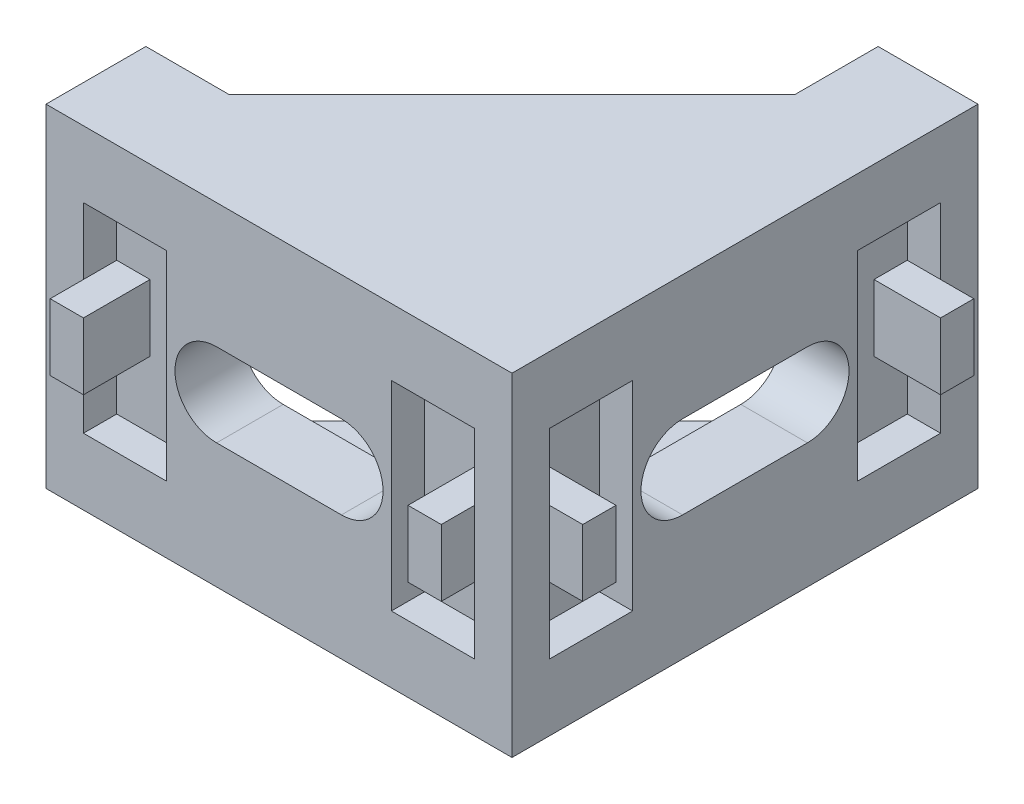
SolidWorks part; units mm, degrees
ref_plane "Front Plane" through (0, 0, 0) normal (0, 0, 1) x (1, 0, 0)
ref_plane "Top Plane" through (0, 0, 0) normal (0, 1, 0) x (1, 0, 0)
ref_plane "Right Plane" through (0, 0, 0) normal (1, 0, 0) x (0, 0, -1)
sketch "Sketch1" plane through (0, 0, 0) normal (0, 1, 0) x (1, 0, 0)
  line L0 (-28, 0) -> (0, 0)
  line L1 (0, 0) -> (0, 28)
  line L2 (0, 28) -> (-6, 28)
  line L3 (-6, 28) -> (-6, 23)
  line L4 (-6, 23) -> (-23, 6)
  line L5 (-23, 6) -> (-28, 6)
  line L6 (-28, 6) -> (-28, 0)
  dimension "D1" = 28
  dimension "D2" = 28
  dimension "D3" = 6
  dimension "D4" = 6
  dimension "D5" = 5
  dimension "D6" = 5
extrude "Boss-Extrude1" add sketch "Sketch1" along normal blind 20
sketch "Sketch2" plane through (0, 0, -28) normal (0, 0, -1) x (-1, 0, 0)
  line L0 (0, 0) -> (6, 0) construction
  line L1 (4, 17) -> (28, 17)
  line L2 (4, 17) -> (4, 3)
  line L3 (4, 3) -> (28, 3)
  line L4 (28, 17) -> (28, 3)
  line L5 (6, 20) -> (23, 20) construction
  line L6 (6, 20) -> (6, 0) construction
  line L7 (23, 20) -> (23, 0) construction
  dimension "D1" = 3
  dimension "D2" = 3
  dimension "D3" = 2
  dimension "D4" = 5
extrude "Cut-Extrude1" cut sketch "Sketch2" against normal blind 24
sketch "Sketch3" plane through (0, 0, 0) normal (0, 0, 1) x (1, 0, 0)
  line L0 (-28, 20) -> (-28, 0) construction
  line L1 (-25.75, 4) -> (-20.75, 4)
  line L2 (-25.75, 4) -> (-25.75, 16)
  line L3 (-25.75, 16) -> (-20.75, 16)
  line L4 (-20.75, 4) -> (-20.75, 16)
  line L5 (-28, 20) -> (0, 20) construction
  line L6 (-28, 0) -> (0, 0) construction
  line L7 (-14, 20) -> (-14, 0) construction
  line L8 (-7.25, 4) -> (-7.25, 16)
  line L9 (-2.25, 16) -> (-7.25, 16)
  line L10 (-2.25, 4) -> (-2.25, 16)
  line L11 (-2.25, 4) -> (-7.25, 4)
  dimension "D1" = 2.25
  dimension "D2" = 4
  dimension "D3" = 4
  dimension "D4" = 5
extrude "Cut-Extrude2" cut sketch "Sketch3" against normal blind 2
sketch "Sketch4" plane through (0, 0, -2) normal (0, 0, 1) x (1, 0, 0)
  line L0 (-25.75, 16) -> (-25.75, 4) construction
  line L1 (-25.75, 12) -> (-23.75, 12)
  line L2 (-25.75, 12) -> (-25.75, 8)
  line L3 (-25.75, 8) -> (-23.75, 8)
  line L4 (-23.75, 12) -> (-23.75, 8)
  line L5 (-20.75, 16) -> (-25.75, 16) construction
  line L6 (-14, 20) -> (-14, 0) construction
  line L7 (-28, 20) -> (0, 20) construction
  line L8 (-28, 0) -> (0, 0) construction
  line L9 (-4.25, 12) -> (-4.25, 8)
  line L10 (-2.25, 8) -> (-4.25, 8)
  line L11 (-2.25, 12) -> (-2.25, 8)
  line L12 (-2.25, 12) -> (-4.25, 12)
  dimension "D1" = 2
  dimension "D2" = 4
  dimension "D3" = 4
extrude "Boss-Extrude2" add sketch "Sketch4" along normal blind 4
ref_plane "Plane5" through (0, 0, 0) normal (-0.7071, 0, 0.7071) x (0.7071, 0, 0.7071)
mirror "Mirror11" about plane through (0, 0, 0) normal (-0.7071, 0, 0.7071) of "Cut-Extrude2", "Boss-Extrude2"
sketch "Sketch5" plane through (0, 0, -4) normal (0, 0, -1) x (-1, 0, 0)
  line L0 (10.25, 10) -> (17.75, 10) construction
  line L1 (10.25, 12.5) -> (17.75, 12.5)
  line L2 (10.25, 7.5) -> (17.75, 7.5)
  line L4 (28, 3) -> (28, 17) construction
  arc A0 (10.25, 12.5) -> (10.25, 7.5) centre (10.25, 10) ccw
  arc A1 (17.75, 7.5) -> (17.75, 12.5) centre (17.75, 10) ccw
  point P2 (14, 10)
  dimension "D1" = 2.5
  dimension "D3" = 17.75
  dimension "D2" = 7.5
extrude "Cut-Extrude3" cut sketch "Sketch5" against normal up to next
mirror "Mirror12" about plane through (0, 0, 0) normal (-0.7071, 0, 0.7071) of "Cut-Extrude3"
